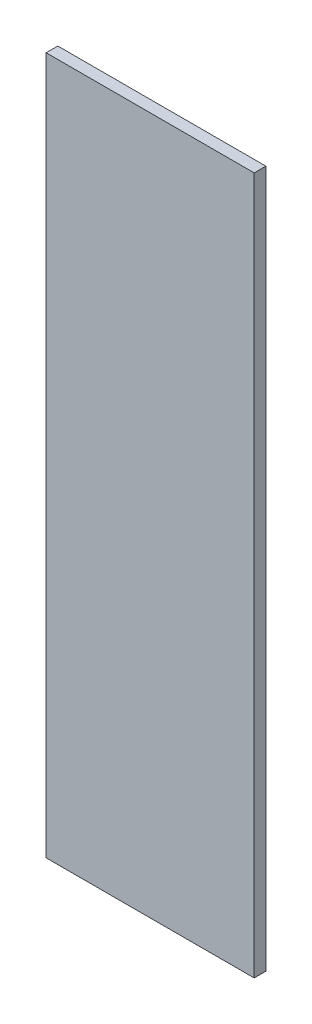
SolidWorks part; units mm, degrees
material "ABS"
ref_plane "X-Y Datum" through (0, 0, 0) normal (0, 0, 1) x (1, 0, 0)
ref_plane "X-Z Datum" through (0, 0, 0) normal (0, 1, 0) x (1, 0, 0)
ref_plane "Y-Z Datum" through (0, 0, 0) normal (1, 0, 0) x (0, 0, -1)
sketch "Sketch1" plane through (0, 0, 0) normal (0, 0, 1) x (1, 0, 0)
  line L1 (83.3851, 204.1965) -> (139.9839, 204.1965)
  line L2 (83.3851, 204.1965) -> (83.3851, 14.5405)
  line L3 (83.3851, 14.5405) -> (139.9839, 14.5405)
  line L4 (139.9839, 204.1965) -> (139.9839, 14.5405)
extrude "Boss-Extrude1" add sketch "Sketch1" along normal blind 3.175
